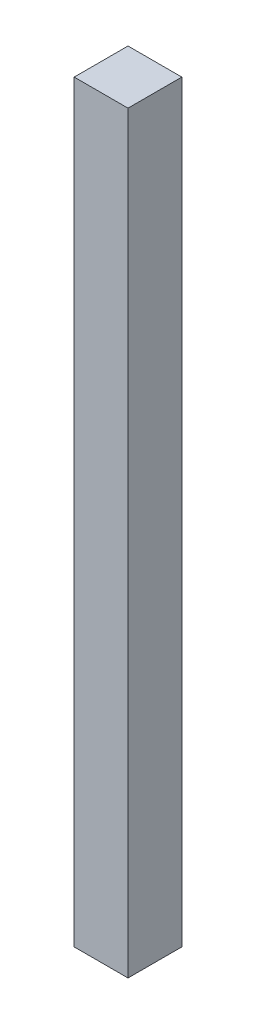
SolidWorks part; units mm, degrees
ref_plane "Front Plane" through (0, 0, 0) normal (0, 0, 1) x (1, 0, 0)
ref_plane "Top Plane" through (0, 0, 0) normal (0, 1, 0) x (1, 0, 0)
ref_plane "Right Plane" through (0, 0, 0) normal (1, 0, 0) x (0, 0, -1)
sketch "Sketch1" plane through (0, 0, 0) normal (0, 1, 0) x (1, 0, 0)
  line L1 (-10, 10) -> (10, 10)
  line L2 (-10, 10) -> (-10, -10)
  line L3 (-10, -10) -> (10, -10)
  line L4 (10, 10) -> (10, -10)
  line L5 (-10, 10) -> (10, -10) construction
  line L6 (-10, -10) -> (10, 10) construction
  point P0 (0, 0)
  dimension "D1" = 20
  dimension "D2" = 20
extrude "Boss-Extrude1" add sketch "Sketch1" along normal blind 280
